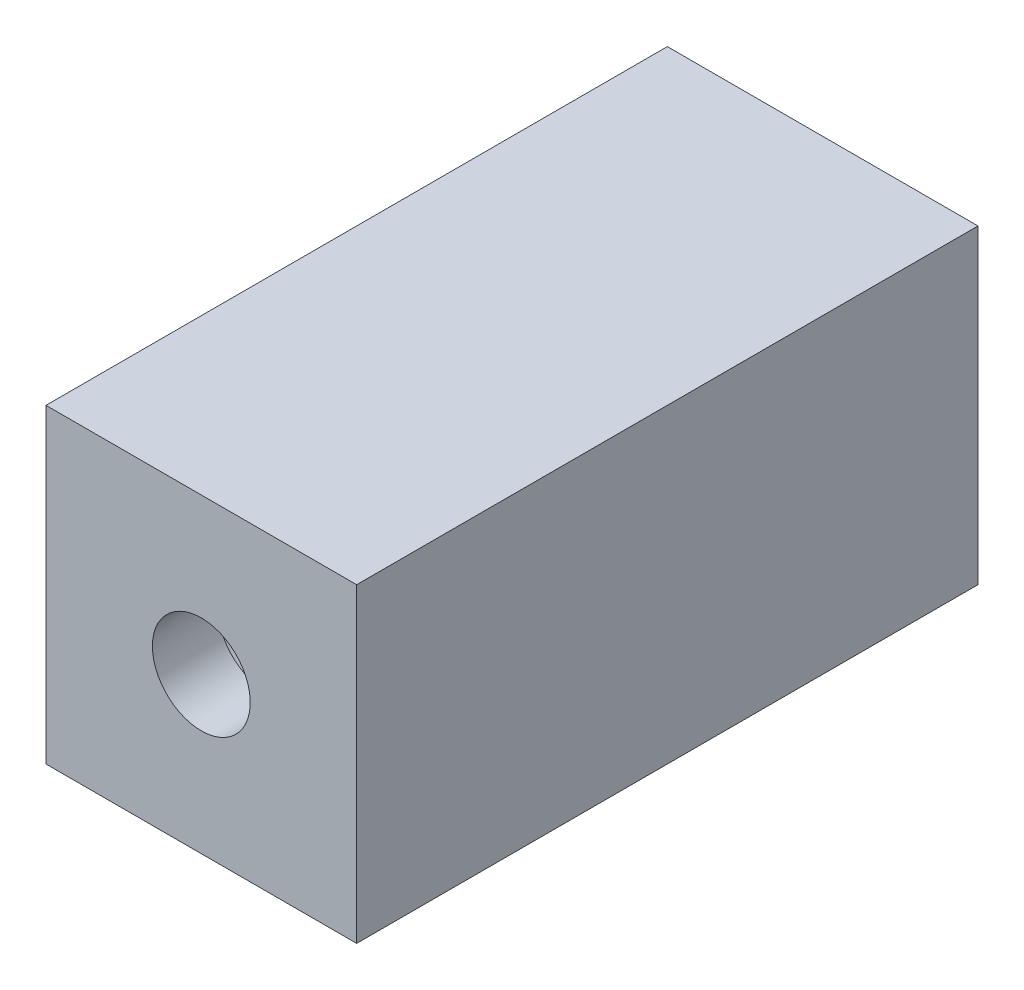
SolidWorks part; units mm, degrees
ref_plane "Front Plane" through (0, 0, 0) normal (0, 0, 1) x (1, 0, 0)
ref_plane "Top Plane" through (0, 0, 0) normal (0, 1, 0) x (1, 0, 0)
ref_plane "Right Plane" through (0, 0, 0) normal (1, 0, 0) x (0, 0, -1)
sketch "Sketch1" plane through (0, 0, 0) normal (1, 0, 0) x (0, 0, -1)
  line L1 (25.4, -12.7) -> (-25.4, -12.7)
  line L2 (25.4, -12.7) -> (25.4, 12.7)
  line L3 (25.4, 12.7) -> (-25.4, 12.7)
  line L4 (-25.4, -12.7) -> (-25.4, 12.7)
  line L5 (25.4, -12.7) -> (-25.4, 12.7) construction
  line L6 (25.4, 12.7) -> (-25.4, -12.7) construction
  point P0 (0, 0)
  dimension "D1" = 50.8
  dimension "D2" = 25.4
extrude "Boss-Extrude1" add sketch "Sketch1" along normal blind 25.4
sketch "Sketch2" plane through (0, 0, -25.4) normal (0, 0, -1) x (-1, 0, 0)
  line L0 (-12.7, 12.7) -> (-12.7, -12.7) construction
  line L1 (-25.4, 12.7) -> (0, 12.7) construction
  line L2 (-25.4, -12.7) -> (0, -12.7) construction
  line L3 (-25.4, 0) -> (0, 0) construction
  line L4 (-25.4, -12.7) -> (-25.4, 12.7) construction
  circle A0 centre (-12.7, 0) radius 4
  dimension "D1" = 8
extrude "Cut-Extrude1" cut sketch "Sketch2" against normal blind 50.8
ref_plane "Plane1" through (0, 0, 0) normal (0, 1, 0) x (1, 0, 0)
sketch "Sketch3" plane through (0, 0, 0) normal (0, 1, 0) x (1, 0, 0)
  line L0 (12.7, -25.4) -> (12.7, 25.4) construction
  line L1 (25.4, -25.4) -> (0, -25.4) construction
  line L2 (25.4, 25.4) -> (0, 25.4) construction
  line L3 (25.4, 0) -> (22.7, 0) construction
  line L4 (25.4, 25.4) -> (25.4, -25.4) construction
  line L5 (25.4, -25.6) -> (22.7, -25.6) construction
  line L6 (0, 25.4) -> (0, -25.4) construction
  line L7 (12.7, -25.4) -> (12.7, 18.5118)
  line L8 (2.7, 18.5118) -> (22.7, 18.5118)
  line L9 (2.7, 18.5118) -> (2.7, -20.0297)
  line L10 (2.7, -20.0297) -> (22.7, -20.0297)
  line L11 (22.7, 18.5118) -> (22.7, -20.0297)
  line L12 (2.7, 18.5118) -> (12.7, -7.2377) construction
  line L13 (2.7, -20.0297) -> (12.7, -7.2377) construction
  line L14 (16.1173, -2.8662) -> (16.1873, -2.7768) construction
  line L15 (12.7, -25.6) -> (0, -25.6) construction
  line L16 (12.7, 0) -> (0, 0) construction
  point P15 (12.7, -7.2377)
  point P28 (12.7, -7.2377)
  dimension "D1" = 51
  dimension "D2" = 20
revolve "Cut-Revolve2" cut sketch "Sketch3" angle 360 about L7
